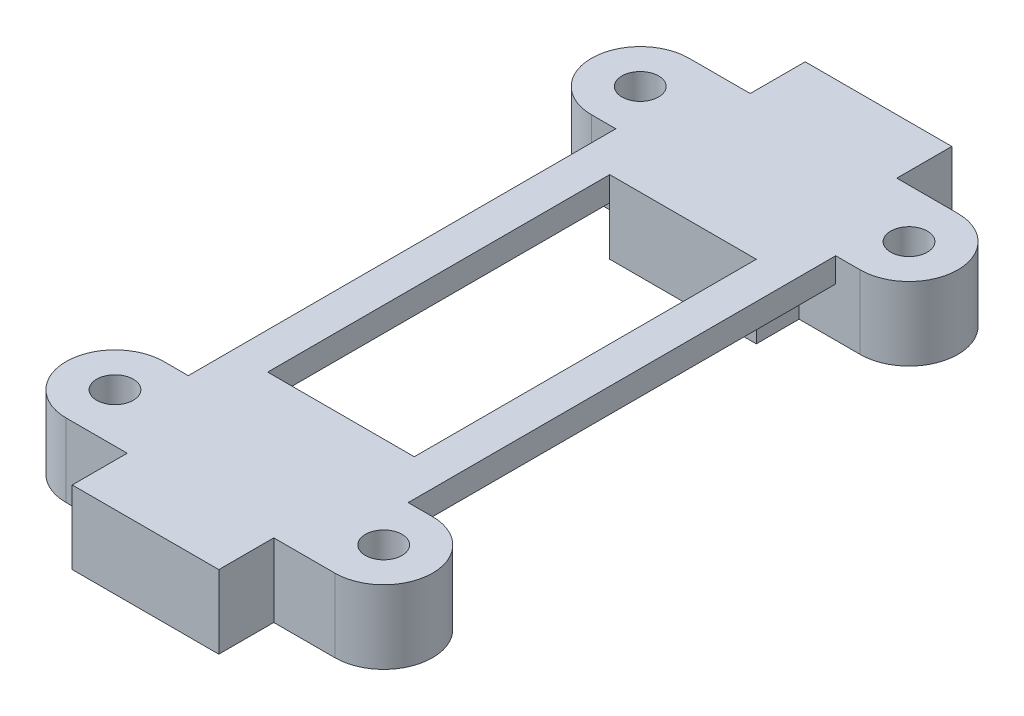
SolidWorks part; units mm, degrees
ref_plane "Front Plane" through (0, 0, 0) normal (0, 0, 1) x (1, 0, 0)
ref_plane "Top Plane" through (0, 0, 0) normal (0, 1, 0) x (1, 0, 0)
ref_plane "Right Plane" through (0, 0, 0) normal (1, 0, 0) x (0, 0, -1)
sketch "Sketch1" plane through (0, 0, 0) normal (0, 1, 0) x (1, 0, 0)
  line L0 (0, 0) -> (0, -43) construction
  line L1 (11, -4) -> (-11, -4)
  line L2 (11, -4) -> (11, 4) construction
  line L3 (11, 4) -> (-11, 4)
  line L4 (-11, -4) -> (-11, 4) construction
  line L5 (11, -4) -> (-11, 4) construction
  line L6 (11, 4) -> (-11, -4) construction
  line L7 (6, 4) -> (-6, 4)
  line L8 (6, 4) -> (6, 8.5)
  line L9 (6, 8.5) -> (-6, 8.5)
  line L10 (-6, 4) -> (-6, 8.5)
  line L11 (6, -4) -> (-6, -4)
  line L12 (6, -4) -> (6, -7.5)
  line L13 (6, -7.5) -> (-6, -7.5)
  line L14 (-6, -4) -> (-6, -7.5)
  line L15 (-16.1697, -21.5) -> (16.1697, -21.5) construction
  line L16 (6, -47) -> (6, -51.5)
  line L17 (6, -51.5) -> (-6, -51.5)
  line L18 (-6, -47) -> (-6, -51.5)
  line L19 (11, -47) -> (-11, -47) construction
  line L20 (11, -39) -> (-11, -39) construction
  line L21 (6, -39) -> (6, -35.5)
  line L22 (-6, -39) -> (-6, -35.5)
  line L23 (6, -35.5) -> (-6, -35.5)
  line L24 (-11, -39) -> (-6, -39)
  line L25 (6, -39) -> (11, -39)
  line L26 (-11, -47) -> (-6, -47)
  line L27 (6, -47) -> (11, -47)
  arc A0 (11, 4) -> (11, -4) centre (11, 0) cw
  arc A1 (-11, -4) -> (-11, 4) centre (-11, 0) cw
  circle A2 centre (11, 0) radius 1.5
  circle A3 centre (-11, 0) radius 1.5
  circle A4 centre (-11, -43) radius 1.5
  circle A5 centre (11, -43) radius 1.5
  arc A6 (11, -47) -> (11, -39) centre (11, -43) ccw
  arc A7 (-11, -39) -> (-11, -47) centre (-11, -43) ccw
  point P0 (0, 0)
  point P12 (0, 8.5)
  point P13 (0, 4)
  point P24 (0, -21.5)
  point P25 (0, -21.5)
  dimension "D3" = 4
  dimension "D6" = 3
  dimension "D1" = 22
  dimension "D2" = 8
  dimension "D4" = 12
  dimension "D5" = 4.5
  dimension "D7" = 12
  dimension "D8" = 3.5
  dimension "D9" = 43
extrude "Boss-Extrude1" add sketch "Sketch1" along normal blind 6 contours A1 L1 A0 L3 A3 A2 | L10 L3 L8 L9 | L12 L11 L14 L13 | L27 A6 L25 L21 L23 L22 L24 A7 L26 L18 L17 L16 | A4 | A5
sketch "Sketch3" plane through (0, 6, 0) normal (0, 1, 0) x (1, 0, 0)
  line L5 (6, -39) -> (11, -39) construction
  line L6 (6, -4) -> (9, -4)
  line L7 (6, -4) -> (6, -39)
  line L8 (6, -39) -> (9, -39)
  line L9 (9, -4) -> (9, -39)
  line L10 (-11, -39) -> (-6, -39) construction
  line L11 (-6, -4) -> (-9, -4)
  line L12 (-6, -4) -> (-6, -39)
  line L13 (-6, -39) -> (-9, -39)
  line L14 (-9, -4) -> (-9, -39)
  dimension "D1" = 3
  dimension "D2" = 3
extrude "Boss-Extrude2" add sketch "Sketch3" against normal blind 2
